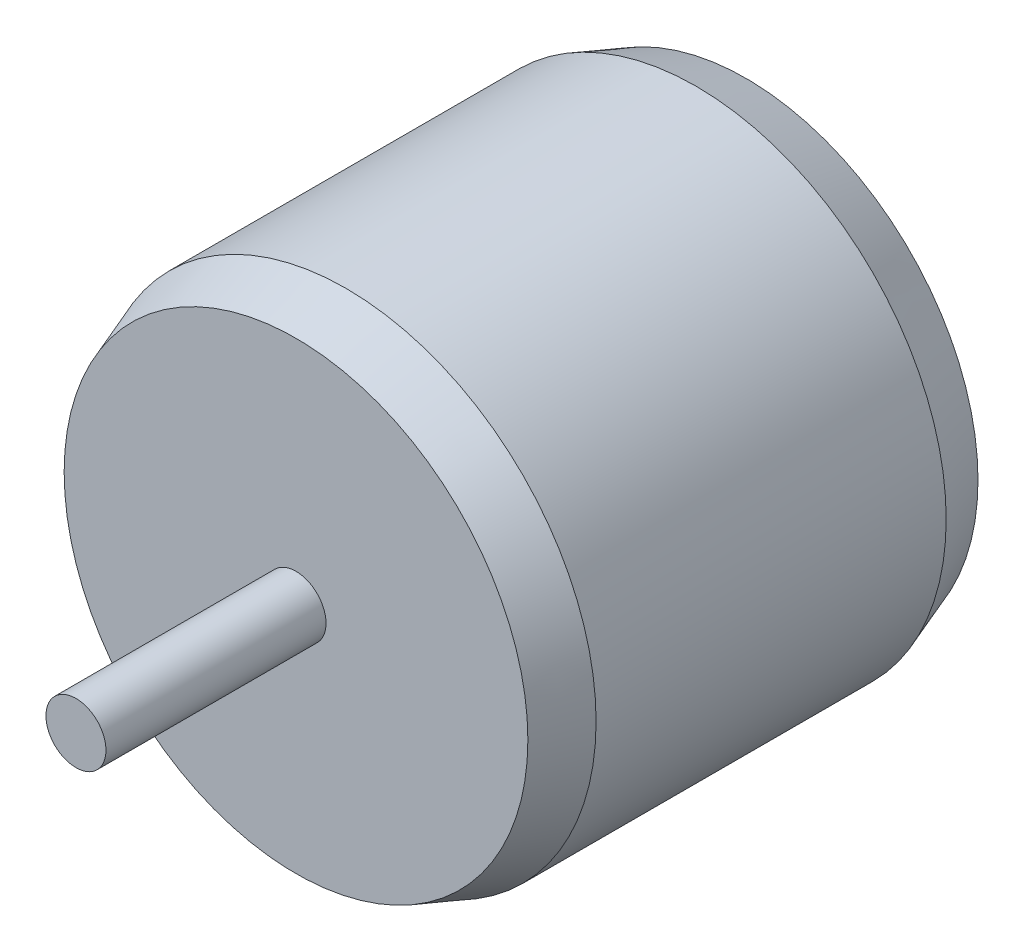
SolidWorks part; units mm, degrees
ref_plane "Front Plane" through (0, 0, 0) normal (0, 0, 1) x (1, 0, 0)
ref_plane "Top Plane" through (0, 0, 0) normal (0, 1, 0) x (1, 0, 0)
ref_plane "Right Plane" through (0, 0, 0) normal (1, 0, 0) x (0, 0, -1)
sketch "Sketch1" plane through (0, 0, 0) normal (0, 0, 1) x (1, 0, 0)
  circle A0 centre (0, 0) radius 25
  dimension "D1" = 50
extrude "Boss-Extrude1" add sketch "Sketch1" along normal blind 45
chamfer "Chamfer1" distance 5 angle 20 2 edges at (25, 0, 0) (25, 0, 45)
sketch "Sketch2" plane through (0, 0, 45) normal (0, 0, 1) x (1, 0, 0)
  circle A0 centre (0, 0) radius 3
  dimension "D1" = 6
extrude "Boss-Extrude2" add sketch "Sketch2" along normal offset from surface (22 mm away) 67 up to face at (23.1801, 0, 0)
sketch "Sketch3" plane through (0, 0, 0) normal (0, 0, -1) x (-1, 0, 0)
  circle A0 centre (0, 0) radius 3
  dimension "D1" = 6
extrude "Boss-Extrude3" add sketch "Sketch3" along normal blind 2
sketch "Sketch4" plane through (0, 0, 0) normal (0, 0, -1) x (-1, 0, 0)
  circle A0 centre (0, 0) radius 10 construction
  point P3 (0, 10)
  dimension "D1" = 20
hole_wizard "Tap Drill for M3x0.5 Tap1" positions "Sketch4" profile "Sketch5" hole size "M3x0.5" standard "ANSI Metric"
sketch "Sketch5" plane through (0, 10, 0) normal (1, 0, 0) x (0, 1, 0)
  line L0 (0, 0) -> (0, 10.7511)
  line L1 (0, 10.7511) -> (1.25, 10)
  line L2 (1.25, 10) -> (1.25, 0)
  line L5 (1.25, 0) -> (0, 0)
  line L10 (0, 10.7511) -> (-1.25, 10) construction
  line L11 (0, -6.35) -> (0, 107.95) construction
  dimension "Hole Dia." = 2.5
  dimension "Hole Depth" = 10
  dimension "Drill Angle" = 118
pattern_circular "CirPattern1" count 4 over 360 about axis through (0, 0, 0) along (0, 0, 1) of "Tap Drill for M3x0.5 Tap1"
